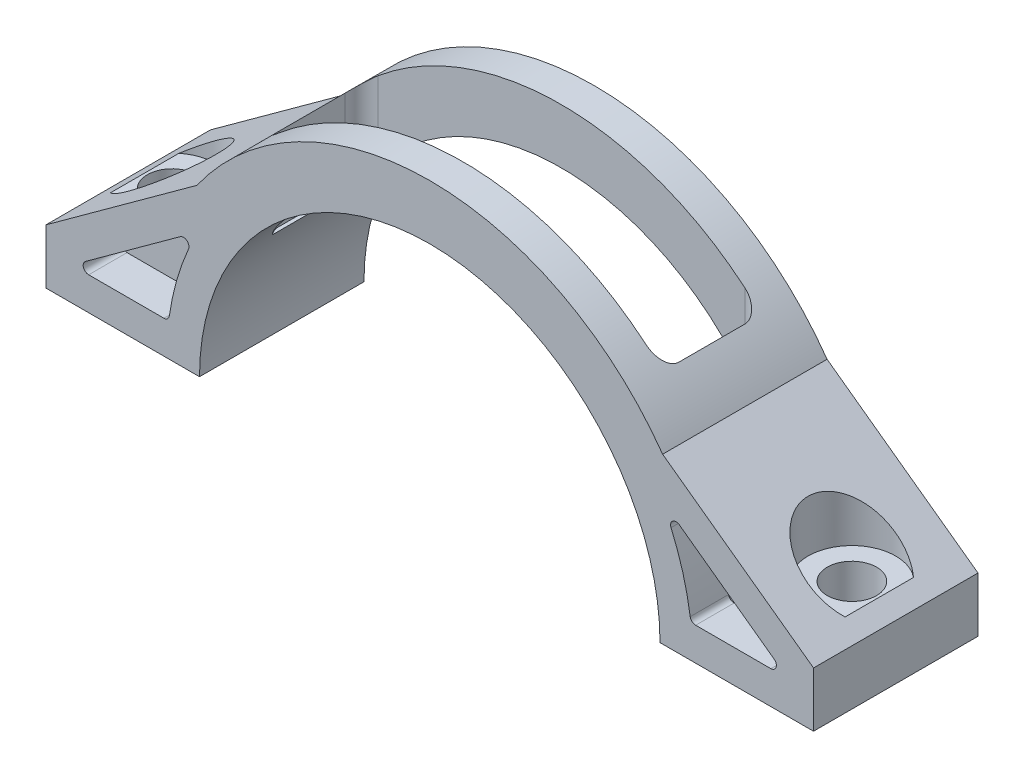
SolidWorks part; units mm, degrees
ref_plane "Alzado" through (0, 0, 0) normal (0, 0, 1) x (1, 0, 0)
ref_plane "Planta" through (0, 0, 0) normal (0, 1, 0) x (1, 0, 0)
ref_plane "Vista lateral" through (0, 0, 0) normal (1, 0, 0) x (0, 0, -1)
sketch "Croquis1" plane through (0, 0, 0) normal (0, 0, 1) x (1, 0, 0)
  line L0 (-26, 0) -> (-21, 0)
  line L5 (21, 0) -> (26, 0)
  arc A0 (26, 0) -> (-26, 0) centre (0, 0) ccw
  arc A2 (21, 0) -> (-21, 0) centre (0, 0) ccw
  point P0 (0, 0)
  dimension "D3" = 21
  dimension "D2" = 26
  dimension "D1" = 52
extrude "Saliente-Extruir1" add sketch "Croquis1" along normal mid plane 15
sketch "Croquis2" plane through (0, 0, 0) normal (0, 0, 1) x (1, 0, 0)
  line L0 (26, 0) -> (35, 0)
  line L1 (35, 0) -> (35, 5)
  line L2 (35, 5) -> (21.2368, 15)
  arc A0 (26, 0) -> (-26, 0) centre (0, 0) ccw construction
  arc A1 (26, 0) -> (21.2368, 15) centre (0, 0) ccw
  dimension "D1" = 9
  dimension "D2" = 5
  dimension "D3" = 15
extrude "Saliente-Extruir2" add sketch "Croquis2" along normal mid plane 15
sketch "Croquis3" plane through (0, 0, 0) normal (0, -1, 0) x (1, 0, 0)
  line L0 (21, -7.5) -> (35, -7.5) construction
  line L1 (35, 7.5) -> (35, -7.5) construction
  circle A0 centre (31, 0) radius 2.25
  dimension "D3" = 4.5
  dimension "D1" = 7.5
  dimension "D2" = 4
extrude "Cortar-Extruir1" cut sketch "Croquis3" against normal through all
ref_plane "Plano1" through (0, 6.09, 0) normal (0, -1, 0) x (-1, 0, 0)
sketch "Croquis4" plane through (0, 6.09, 0) normal (0, -1, 0) x (-1, 0, 0)
  circle A0 centre (-31, 0) radius 4
  dimension "D1" = 8
extrude "Cortar-Extruir2" cut sketch "Croquis4" against normal through all
mirror "Simetría1" about plane through (0, 0, 0) normal (1, 0, 0) of "Cortar-Extruir2", "Saliente-Extruir2", "Cortar-Extruir1"
sketch "Croquis6" plane through (0, 0, 7.5) normal (0, 0, 1) x (1, 0, 0)
  line L5 (32, 0) -> (32, 3.4715)
  line L6 (32, 3.4715) -> (19.4734, 12.573)
  line L8 (31.404, 3.9045) -> (22.7556, 10.1882)
  line L10 (23.8118, 3) -> (35, 3)
  line L11 (24.2487, 3) -> (31.1101, 3)
  arc A1 (23.7538, 3.4286) -> (24.2487, 3) centre (24.2487, 3.5) ccw
  arc A2 (23.8118, 3) -> (-24, 0) centre (0, 0) ccw
  arc A3 (23.7538, 3.4286) -> (22.0033, 9.584) centre (0, 0) ccw
  arc A4 (22.0033, 9.584) -> (22.7556, 10.1882) centre (22.4617, 9.7837) cw
  arc A5 (31.1101, 3) -> (31.404, 3.9045) centre (31.1101, 3.5) ccw
  dimension "D3" = 0.5
  dimension "D4" = 0.5
  dimension "D1" = 3
  dimension "D2" = 3
extrude "Cortar-Extruir3" cut sketch "Croquis6" against normal blind 3.5
mirror "Simetría2" about plane through (0, 0, 0) normal (0, 0, 1) of "Cortar-Extruir3"
ref_plane "Plano2" through (0, 26, 0) normal (0, 1, 0) x (1, 0, 0)
sketch "Croquis8" plane through (0, 26, 0) normal (0, 1, 0) x (1, 0, 0)
  line L17 (-18.2368, -4.5) -> (18.2368, -4.5)
  line L18 (18.2368, -4.5) -> (18.2368, 4.5)
  line L19 (-18.2368, 4.5) -> (-18.2368, -4.5)
  line L20 (18.2368, 4.5) -> (-18.2368, 4.5)
  line L21 (-16.7368, -4.5) -> (16.7368, -4.5)
  line L22 (18.2368, -3) -> (18.2368, 3)
  line L23 (-18.2368, 3) -> (-18.2368, -3)
  line L24 (16.7368, 4.5) -> (-16.7368, 4.5)
  arc A0 (-16.7368, -4.5) -> (-18.2368, -3) centre (-16.7368, -3) cw
  arc A1 (-18.2368, 3) -> (-16.7368, 4.5) centre (-16.7368, 3) cw
  arc A2 (18.2368, 3) -> (16.7368, 4.5) centre (16.7368, 3) ccw
  arc A3 (16.7368, -4.5) -> (18.2368, -3) centre (16.7368, -3) ccw
  dimension "D2" = 1.5
  dimension "D1" = 3
extrude "Cortar-Extruir4" cut sketch "Croquis8" against normal blind 15
mirror "Simetría3" about plane through (0, 0, 0) normal (1, 0, 0) of "Cortar-Extruir3", "Simetría2"
